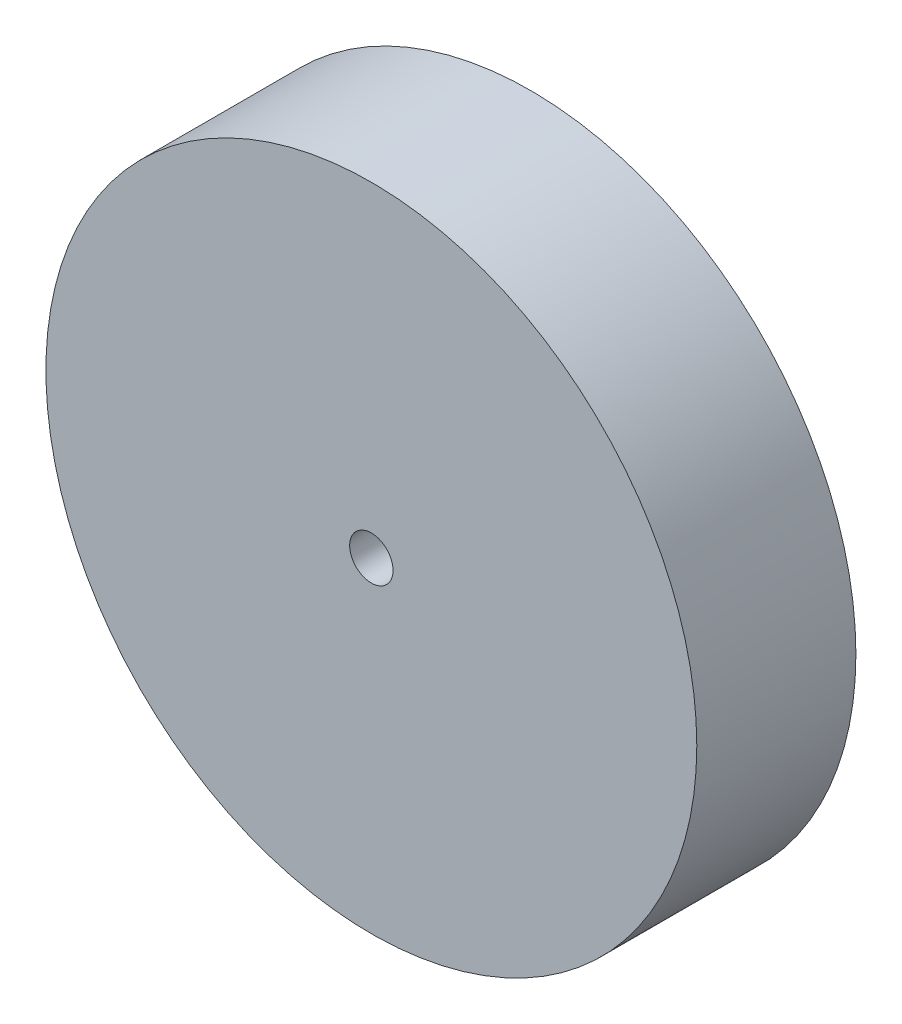
SolidWorks part; units mm, degrees
ref_plane "Front Plane" through (0, 0, 0) normal (0, 0, 1) x (1, 0, 0)
ref_plane "Top Plane" through (0, 0, 0) normal (0, 1, 0) x (1, 0, 0)
ref_plane "Right Plane" through (0, 0, 0) normal (1, 0, 0) x (0, 0, -1)
sketch "Sketch1" plane through (0, 0, 0) normal (0, 0, 1) x (1, 0, 0)
  circle A0 centre (0, 0) radius 22.5
  dimension "D1" = 45
extrude "Boss-Extrude1" add sketch "Sketch1" along normal blind 11
sketch "Sketch2" plane through (0, 0, 11) normal (0, 0, 1) x (1, 0, 0)
  circle A0 centre (0, 0) radius 1.5
  dimension "D1" = 3
extrude "Cut-Extrude1" cut sketch "Sketch2" against normal through all
